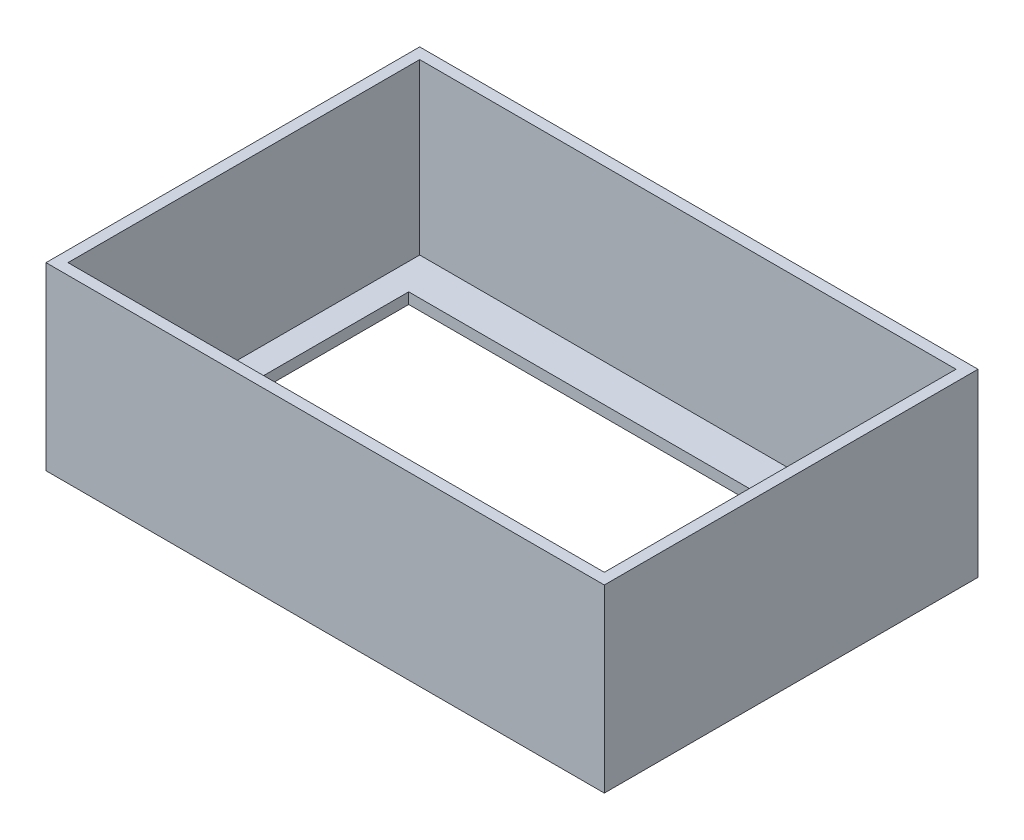
SolidWorks part; units mm, degrees
ref_plane "Front Plane" through (0, 0, 0) normal (0, 0, 1) x (1, 0, 0)
ref_plane "Top Plane" through (0, 0, 0) normal (0, 1, 0) x (1, 0, 0)
ref_plane "Right Plane" through (0, 0, 0) normal (1, 0, 0) x (0, 0, -1)
sketch "Sketch1" plane through (0, 0, 0) normal (0, 1, 0) x (1, 0, 0)
  line L1 (0, 0) -> (127, 0)
  line L2 (0, 0) -> (0, 85)
  line L3 (0, 85) -> (127, 85)
  line L4 (127, 0) -> (127, 85)
extrude "Boss-Extrude1" add sketch "Sketch1" along normal blind 2.5
sketch "Sketch2" plane through (0, 2.5, 0) normal (0, 1, 0) x (1, 0, 0)
  line L0 (0, 85) -> (127, 85)
  line L1 (127, 85) -> (127, 0)
  line L2 (127, 0) -> (0, 0)
  line L3 (0, 0) -> (0, 85)
  line L5 (2.5, 82.5) -> (124.5, 82.5)
  line L6 (2.5, 82.5) -> (2.5, 2.5)
  line L7 (2.5, 2.5) -> (124.5, 2.5)
  line L8 (124.5, 82.5) -> (124.5, 2.5)
  dimension "D1" = 2.5
  dimension "D2" = 2.5
  dimension "D3" = 2.5
  dimension "D4" = 2.5
extrude "Boss-Extrude2" add sketch "Sketch2" along normal blind 38.5
sketch "Sketch3" plane through (0, 0, 0) normal (0, -1, 0) x (-1, 0, 0)
  line L0 (-127, 85) -> (0, 85) construction
  line L1 (-8.5, 5.5) -> (-118.5, 5.5)
  line L2 (-8.5, 5.5) -> (-8.5, 74)
  line L3 (-8.5, 74) -> (-118.5, 74)
  line L4 (-118.5, 5.5) -> (-118.5, 74)
  line L6 (0, 0) -> (-127, 0) construction
  line L7 (-127, 0) -> (-127, 85) construction
  line L8 (0, 85) -> (0, 0) construction
  dimension "D1" = 11
  dimension "D2" = 5.5
  dimension "D3" = 8.5
  dimension "D4" = 8.5
extrude "Cut-Extrude1" cut sketch "Sketch3" against normal blind 2.5
sketch "Sketch6" plane through (0, 0, 0) normal (0, -1, 0) x (-1, 0, 0)
  line L8 (-61.1, 92.6537) -> (-65.9, 92.6537) construction
  line L9 (-61.1, 90.1537) -> (-65.9, 90.1537)
  line L10 (-61.1, 95.1537) -> (-65.9, 95.1537)
  arc A0 (-61.1, 90.1537) -> (-61.1, 95.1537) centre (-61.1, 92.6537) ccw
  arc A2 (-65.9, 95.1537) -> (-65.9, 90.1537) centre (-65.9, 92.6537) ccw
  point P1 (-63.5, 92.6537)
